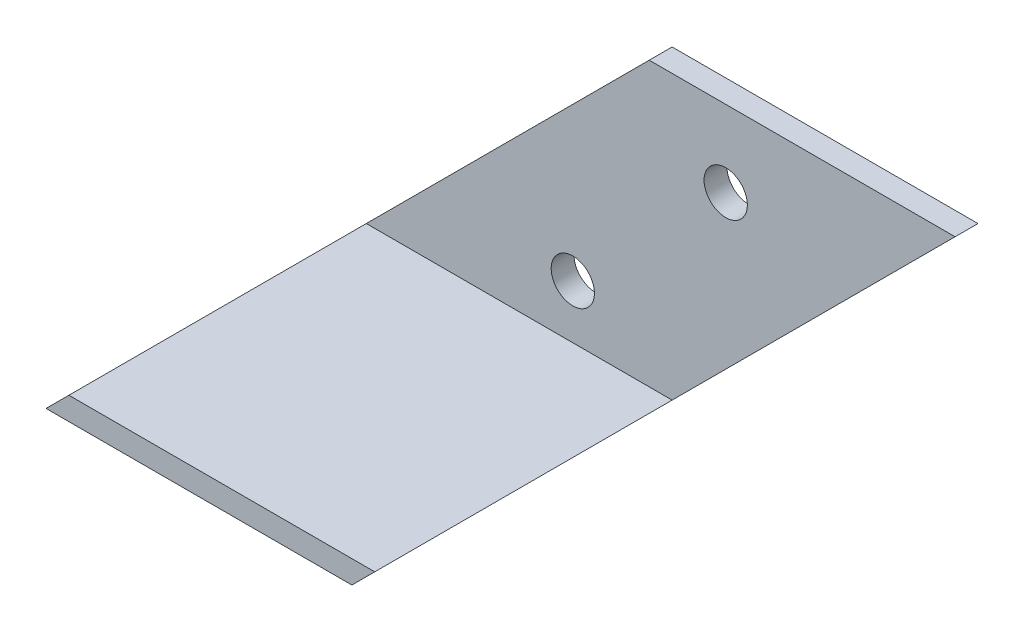
SolidWorks part; units mm, degrees
ref_plane "Front Plane" through (0, 0, 0) normal (0, 0, 1) x (1, 0, 0)
ref_plane "Top Plane" through (0, 0, 0) normal (0, 1, 0) x (1, 0, 0)
ref_plane "Right Plane" through (0, 0, 0) normal (1, 0, 0) x (0, 0, -1)
sketch "Sketch1" plane through (0, 0, 0) normal (0, 0, 1) x (1, 0, 0)
  line L1 (0, 0) -> (45, 0)
  line L2 (0, 0) -> (0, 21.21)
  line L3 (0, 21.21) -> (45, 21.21)
  line L4 (45, 0) -> (45, 21.21)
  dimension "D1" = 45
  dimension "D2" = 21.21
extrude "Boss-Extrude1" add sketch "Sketch1" along normal blind 1.5875
sketch "Sketch2" plane through (0, 0, 1.5875) normal (0, 0, 1) x (1, 0, 0)
  line L0 (0, 21.21) -> (0, 0) construction
  line L1 (45, 0) -> (0, 0)
  line L2 (45, 0) -> (45, 1.5875)
  line L3 (45, 1.5875) -> (0, 1.5875)
  line L4 (0, 0) -> (0, 1.5875)
  dimension "D1" = 1.5875
extrude "Boss-Extrude2" add sketch "Sketch2" along normal blind 20.6257
sketch "Sketch3" plane through (0, 0, 0) normal (0, 0, -1) x (-1, 0, 0)
  line L0 (0, 0) -> (-8.7868, 21.21)
  line L1 (-45, 21.21) -> (0, 21.21) construction
  line L2 (-8.7868, 21.21) -> (-30, 21.21)
  line L3 (-30, 21.21) -> (-15, 0)
  line L4 (0, 0) -> (-45, 0) construction
  line L5 (-30, 21.21) -> (-45, 21.21)
  line L6 (-45, 21.21) -> (-45, 0)
  line L7 (-45, 0) -> (-15, 0)
  line L8 (-8.7868, 21.21) -> (0, 21.21)
  line L9 (0, 21.21) -> (0, 0)
  dimension "D1" = 21.2132
sketch "Sketch5" plane through (0, 0, 0) normal (0, 0, -1) x (-1, 0, 0)
  line L0 (0, 0) -> (-21.21, 21.21)
  line L1 (-8.7868, 21.21) -> (-30, 21.21) construction
  line L2 (-21.21, 21.21) -> (-42.4232, 21.21)
  line L3 (-30, 21.21) -> (-45, 21.21) construction
  line L4 (0, 0) -> (-21.2132, 0)
  line L5 (-45, 0) -> (-15, 0) construction
  line L6 (-21.2132, 0) -> (-42.4232, 21.21)
  line L7 (-42.4232, 21.21) -> (-45, 21.21)
  line L8 (-45, 21.21) -> (-45, 0)
  line L9 (-45, 0) -> (-21.2132, 0)
  line L10 (0, 0) -> (0, 21.21)
  line L11 (0, 21.21) -> (-21.21, 21.21)
  line M4 (0, 0) -> (0, 21.21)
  line M5 (0, 21.21) -> (-45, 21.21)
  line M6 (-45, 21.21) -> (-45, 0)
  line M7 (-45, 0) -> (0, 0)
  dimension "D1" = 21.2132
  dimension "D2" = 21.2132
extrude "Cut-Extrude3" cut sketch "Sketch5" against normal through all contours L0 M4 M5 | L6 M7 M5 M6
sketch "Sketch4" plane through (0, 0, 0) normal (0, 0, -1) x (-1, 0, 0)
  line L0 (-31.8166, 21.21) -> (-10.6066, 0)
  line L1 (-42.4232, 21.21) -> (-21.21, 21.21) construction
  line L2 (0, 0) -> (-21.2132, 0) construction
  line L3 (-10.6066, 0) -> (-21.2116, 10.605)
  line L4 (-21.2116, 10.605) -> (-31.8166, 21.21)
  line L5 (-21.2116, 10.605) -> (-10.6066, 0)
  circle A0 centre (-26.5141, 15.9075) radius 1.5
  circle A2 centre (-15.9091, 5.3025) radius 1.5
extrude "Cut-Extrude4" cut sketch "Sketch4" against normal through all contours L5 A2 | L5 A2 | L4 A0 | L4 A0
